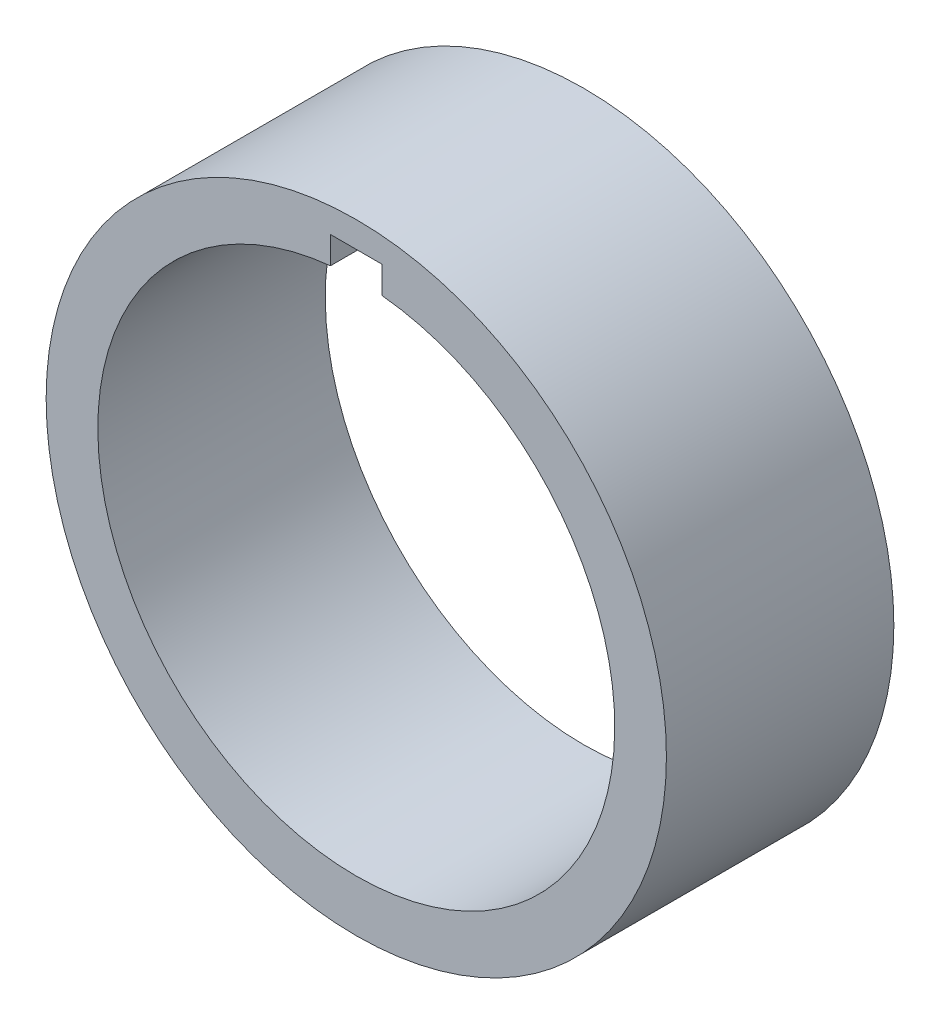
SolidWorks part; units mm, degrees
ref_plane "Front Plane" through (0, 0, 0) normal (0, 0, 1) x (1, 0, 0)
ref_plane "Top Plane" through (0, 0, 0) normal (0, 1, 0) x (1, 0, 0)
ref_plane "Right Plane" through (0, 0, 0) normal (1, 0, 0) x (0, 0, -1)
sketch "Sketch1" plane through (0, 0, 0) normal (0, 0, 1) x (1, 0, 0)
  line L3 (-2.5, 24.8747) -> (-2.5, 27.5)
  line L4 (-2.5, 27.5) -> (2.5, 27.5)
  line L5 (2.5, 27.5) -> (2.5, 24.8747)
  arc A0 (-2.5, 24.8747) -> (2.5, 24.8747) centre (0, 0) ccw
  circle A2 centre (0, 0) radius 30
  point P5 (0, 27.5)
  dimension "D1" = 5
  dimension "D2" = 50
  dimension "D3" = 5
  dimension "D5" = 27.5
extrude "Boss-Extrude1" add sketch "Sketch1" along normal blind 22 contours A2 | A0 L5 L4 L3
